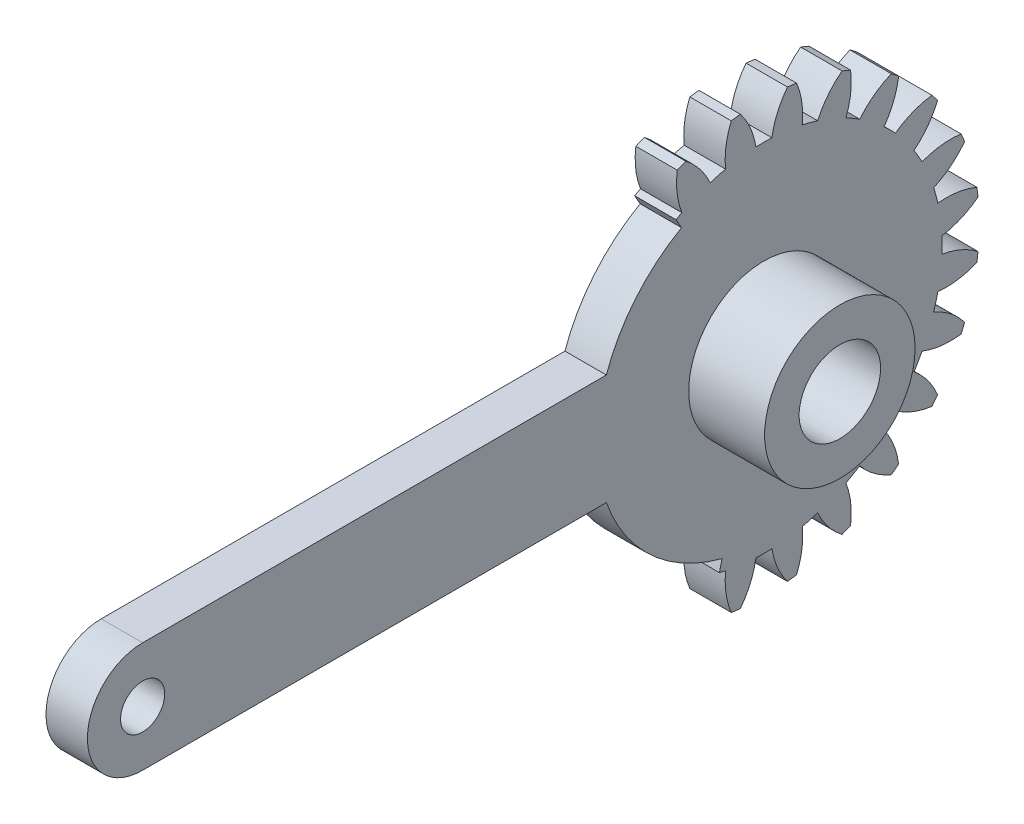
SolidWorks part; units mm, degrees
ref_plane "Front Plane" through (0, 0, 0) normal (0, 0, 1) x (1, 0, 0)
ref_plane "Top Plane" through (0, 0, 0) normal (0, 1, 0) x (1, 0, 0)
ref_plane "Right Plane" through (0, 0, 0) normal (1, 0, 0) x (0, 0, -1)
ref_plane "Plane1" through (3, 0, 0) normal (1, 0, 0) x (0, 0, -1)
sketch "Sketch1" plane through (3, 0, 0) normal (1, 0, 0) x (0, 0, -1)
  circle A0 centre (0, 0) radius 1.6
  arc A1 (-15.5065, 1.7057) -> (-12.8859, 0.5789) centre (-11.9918, 6.2691) ccw
  arc A2 (-12.8859, 0.5789) -> (-12.8859, -0.5789) centre (0, 0) ccw
  arc A3 (-12.8859, -0.5789) -> (-15.5065, -1.7057) centre (-11.9918, -6.2691) ccw
  arc A4 (-15.5065, -1.7057) -> (-15.4196, -2.3658) centre (0, 0) ccw
  arc A5 (-15.4196, -2.3658) -> (-12.5967, -2.7759) centre (-13.2057, 2.9518) ccw
  arc A6 (-12.5967, -2.7759) -> (-12.297, -3.8943) centre (0, 0) ccw
  arc A7 (-12.297, -3.8943) -> (-14.5366, -5.6609) centre (-9.9606, -9.1592) ccw
  arc A8 (-14.5366, -5.6609) -> (-14.2818, -6.2761) centre (0, 0) ccw
  arc A9 (-14.2818, -6.2761) -> (-11.449, -5.9416) centre (-13.5197, -0.5667) ccw
  arc A10 (-11.449, -5.9416) -> (-10.8701, -6.9443) centre (0, 0) ccw
  arc A11 (-10.8701, -6.9443) -> (-12.5761, -9.2304) centre (-7.2506, -11.4251) ccw
  arc A12 (-12.5761, -9.2304) -> (-12.1708, -9.7586) centre (0, 0) ccw
  arc A13 (-12.1708, -9.7586) -> (-9.5211, -8.7024) centre (-12.9124, -4.0465) ccw
  arc A14 (-9.5211, -8.7024) -> (-8.7024, -9.5211) centre (0, 0) ccw
  arc A15 (-8.7024, -9.5211) -> (-9.7586, -12.1708) centre (-4.0465, -12.9124) ccw
  arc A16 (-9.7586, -12.1708) -> (-9.2304, -12.5761) centre (0, 0) ccw
  arc A17 (-9.2304, -12.5761) -> (-6.9443, -10.8701) centre (-11.4251, -7.2506) ccw
  arc A18 (-6.9443, -10.8701) -> (-5.9416, -11.449) centre (0, 0) ccw
  arc A19 (-5.9416, -11.449) -> (-6.2761, -14.2818) centre (-0.5667, -13.5197) ccw
  arc A20 (-6.2761, -14.2818) -> (-5.6609, -14.5366) centre (0, 0) ccw
  arc A21 (-5.6609, -14.5366) -> (-3.8943, -12.297) centre (-9.1592, -9.9606) ccw
  arc A22 (-3.8943, -12.297) -> (-2.7759, -12.5967) centre (0, 0) ccw
  arc A23 (-2.7759, -12.5967) -> (-2.3658, -15.4196) centre (2.9518, -13.2057) ccw
  arc A24 (-2.3658, -15.4196) -> (-1.7057, -15.5065) centre (0, 0) ccw
  arc A25 (-1.7057, -15.5065) -> (-0.5789, -12.8859) centre (-6.2691, -11.9918) ccw
  arc A26 (-0.5789, -12.8859) -> (0.5789, -12.8859) centre (0, 0) ccw
  arc A27 (0.5789, -12.8859) -> (1.7057, -15.5065) centre (6.2691, -11.9918) ccw
  arc A28 (1.7057, -15.5065) -> (2.3658, -15.4196) centre (0, 0) ccw
  arc A29 (2.3658, -15.4196) -> (2.7759, -12.5967) centre (-2.9518, -13.2057) ccw
  arc A30 (2.7759, -12.5967) -> (3.8943, -12.297) centre (0, 0) ccw
  arc A31 (3.8943, -12.297) -> (5.6609, -14.5366) centre (9.1592, -9.9606) ccw
  arc A32 (5.6609, -14.5366) -> (6.2761, -14.2818) centre (0, 0) ccw
  arc A33 (6.2761, -14.2818) -> (5.9416, -11.449) centre (0.5667, -13.5197) ccw
  arc A34 (5.9416, -11.449) -> (6.9443, -10.8701) centre (0, 0) ccw
  arc A35 (6.9443, -10.8701) -> (9.2304, -12.5761) centre (11.4251, -7.2506) ccw
  arc A36 (9.2304, -12.5761) -> (9.7586, -12.1708) centre (0, 0) ccw
  arc A37 (9.7586, -12.1708) -> (8.7024, -9.5211) centre (4.0465, -12.9124) ccw
  arc A38 (8.7024, -9.5211) -> (9.5211, -8.7024) centre (0, 0) ccw
  arc A39 (9.5211, -8.7024) -> (12.1708, -9.7586) centre (12.9124, -4.0465) ccw
  arc A40 (12.1708, -9.7586) -> (12.5761, -9.2304) centre (0, 0) ccw
  arc A41 (12.5761, -9.2304) -> (10.8701, -6.9443) centre (7.2506, -11.4251) ccw
  arc A42 (10.8701, -6.9443) -> (11.449, -5.9416) centre (0, 0) ccw
  arc A43 (11.449, -5.9416) -> (14.2818, -6.2761) centre (13.5197, -0.5667) ccw
  arc A44 (14.2818, -6.2761) -> (14.5366, -5.6609) centre (0, 0) ccw
  arc A45 (14.5366, -5.6609) -> (12.297, -3.8943) centre (9.9606, -9.1592) ccw
  arc A46 (12.297, -3.8943) -> (12.5967, -2.7759) centre (0, 0) ccw
  arc A47 (12.5967, -2.7759) -> (15.4196, -2.3658) centre (13.2057, 2.9518) ccw
  arc A48 (15.4196, -2.3658) -> (15.5065, -1.7057) centre (0, 0) ccw
  arc A49 (15.5065, -1.7057) -> (12.8859, -0.5789) centre (11.9918, -6.2691) ccw
  arc A50 (12.8859, -0.5789) -> (12.8859, 0.5789) centre (0, 0) ccw
  arc A51 (12.8859, 0.5789) -> (15.5065, 1.7057) centre (11.9918, 6.2691) ccw
  arc A52 (15.5065, 1.7057) -> (15.4196, 2.3658) centre (0, 0) ccw
  arc A53 (15.4196, 2.3658) -> (12.5967, 2.7759) centre (13.2057, -2.9518) ccw
  arc A54 (12.5967, 2.7759) -> (12.297, 3.8943) centre (0, 0) ccw
  arc A55 (12.297, 3.8943) -> (14.5366, 5.6609) centre (9.9606, 9.1592) ccw
  arc A56 (14.5366, 5.6609) -> (14.2818, 6.2761) centre (0, 0) ccw
  arc A57 (14.2818, 6.2761) -> (11.449, 5.9416) centre (13.5197, 0.5667) ccw
  arc A58 (11.449, 5.9416) -> (10.8701, 6.9443) centre (0, 0) ccw
  arc A59 (10.8701, 6.9443) -> (12.5761, 9.2304) centre (7.2506, 11.4251) ccw
  arc A60 (12.5761, 9.2304) -> (12.1708, 9.7586) centre (0, 0) ccw
  arc A61 (12.1708, 9.7586) -> (9.5211, 8.7024) centre (12.9124, 4.0465) ccw
  arc A62 (9.5211, 8.7024) -> (8.7024, 9.5211) centre (0, 0) ccw
  arc A63 (8.7024, 9.5211) -> (9.7586, 12.1708) centre (4.0465, 12.9124) ccw
  arc A64 (9.7586, 12.1708) -> (9.2304, 12.5761) centre (0, 0) ccw
  arc A65 (9.2304, 12.5761) -> (6.9443, 10.8701) centre (11.4251, 7.2506) ccw
  arc A66 (6.9443, 10.8701) -> (5.9416, 11.449) centre (0, 0) ccw
  arc A67 (5.9416, 11.449) -> (6.2761, 14.2818) centre (0.5667, 13.5197) ccw
  arc A68 (6.2761, 14.2818) -> (5.6609, 14.5366) centre (0, 0) ccw
  arc A69 (5.6609, 14.5366) -> (3.8943, 12.297) centre (9.1592, 9.9606) ccw
  arc A70 (3.8943, 12.297) -> (2.7759, 12.5967) centre (0, 0) ccw
  arc A71 (2.7759, 12.5967) -> (2.3658, 15.4196) centre (-2.9518, 13.2057) ccw
  arc A72 (2.3658, 15.4196) -> (1.7057, 15.5065) centre (0, 0) ccw
  arc A73 (1.7057, 15.5065) -> (0.5789, 12.8859) centre (6.2691, 11.9918) ccw
  arc A74 (0.5789, 12.8859) -> (-0.5789, 12.8859) centre (0, 0) ccw
  arc A75 (-0.5789, 12.8859) -> (-1.7057, 15.5065) centre (-6.2691, 11.9918) ccw
  arc A76 (-1.7057, 15.5065) -> (-2.3658, 15.4196) centre (0, 0) ccw
  arc A77 (-2.3658, 15.4196) -> (-2.7759, 12.5967) centre (2.9518, 13.2057) ccw
  arc A78 (-2.7759, 12.5967) -> (-3.8943, 12.297) centre (0, 0) ccw
  arc A79 (-3.8943, 12.297) -> (-5.6609, 14.5366) centre (-9.1592, 9.9606) ccw
  arc A80 (-5.6609, 14.5366) -> (-6.2761, 14.2818) centre (0, 0) ccw
  arc A81 (-6.2761, 14.2818) -> (-5.9416, 11.449) centre (-0.5667, 13.5197) ccw
  arc A82 (-5.9416, 11.449) -> (-6.9443, 10.8701) centre (0, 0) ccw
  arc A83 (-6.9443, 10.8701) -> (-9.2304, 12.5761) centre (-11.4251, 7.2506) ccw
  arc A84 (-9.2304, 12.5761) -> (-9.7586, 12.1708) centre (0, 0) ccw
  arc A85 (-9.7586, 12.1708) -> (-8.7024, 9.5211) centre (-4.0465, 12.9124) ccw
  arc A86 (-8.7024, 9.5211) -> (-9.5211, 8.7024) centre (0, 0) ccw
  arc A87 (-9.5211, 8.7024) -> (-12.1708, 9.7586) centre (-12.9124, 4.0465) ccw
  arc A88 (-12.1708, 9.7586) -> (-12.5761, 9.2304) centre (0, 0) ccw
  arc A89 (-12.5761, 9.2304) -> (-10.8701, 6.9443) centre (-7.2506, 11.4251) ccw
  arc A90 (-10.8701, 6.9443) -> (-11.449, 5.9416) centre (0, 0) ccw
  arc A91 (-11.449, 5.9416) -> (-14.2818, 6.2761) centre (-13.5197, 0.5667) ccw
  arc A92 (-14.2818, 6.2761) -> (-14.5366, 5.6609) centre (0, 0) ccw
  arc A93 (-14.5366, 5.6609) -> (-12.297, 3.8943) centre (-9.9606, 9.1592) ccw
  arc A94 (-12.297, 3.8943) -> (-12.5967, 2.7759) centre (0, 0) ccw
  arc A95 (-12.5967, 2.7759) -> (-15.4196, 2.3658) centre (-13.2057, -2.9518) ccw
  arc A96 (-15.4196, 2.3658) -> (-15.5065, 1.7057) centre (0, 0) ccw
  dimension "D1" = 3.2
extrude "Boss-Extrude1" add sketch "Sketch1" against normal blind 3
sketch "Sketch2" plane through (3, 0, 0) normal (1, 0, 0) x (0, 0, -1)
  line L0 (0, -4) -> (-45, -4)
  line L1 (0, 4) -> (-45, 4)
  line L2 (-45, 0) -> (0, 0) construction
  arc A0 (0, -4) -> (0, 4) centre (0, 0) ccw
  arc A1 (-45, 4) -> (-45, -4) centre (-45, 0) ccw
  circle A2 centre (-45, 0) radius 1.6
  circle A3 centre (0, 0) radius 1.75
  dimension "D1" = 45
  dimension "D2" = 4
  dimension "D3" = 4
  dimension "D4" = 3.2
  dimension "D5" = 3.5
extrude "Boss-Extrude2" add sketch "Sketch2" against normal blind 3
sketch "Sketch3" plane through (3, 0, 0) normal (1, 0, 0) x (0, 0, -1)
  line L0 (-11.412, 4) -> (-15.9812, 4)
  line L1 (-12.522, 4) -> (-45, 4) construction
  line L2 (-15.9812, -4) -> (-11.412, -4)
  line L3 (-45, -4) -> (-12.522, -4) construction
  line L5 (-3.0243, -11.7085) -> (-4.12, -15.9507)
  line L6 (-5.966, 10.5186) -> (-8.1276, 14.3297)
  arc A0 (-5.966, 10.5186) -> (-3.0243, -11.7085) centre (0, 0) ccw
  arc A1 (-8.1276, 14.3297) -> (-4.12, -15.9507) centre (0, 0) ccw
extrude "Cut-Extrude1" cut sketch "Sketch3" against normal blind 10
sketch "Sketch4" plane through (3, 0, 0) normal (1, 0, 0) x (0, 0, -1)
  circle A0 centre (0, 0) radius 2.95
  circle A1 centre (0, 0) radius 5.45
  dimension "D1" = 2.5
  dimension "D2" = 5.9
extrude "Boss-Extrude3" add sketch "Sketch4" along normal blind 5.5
